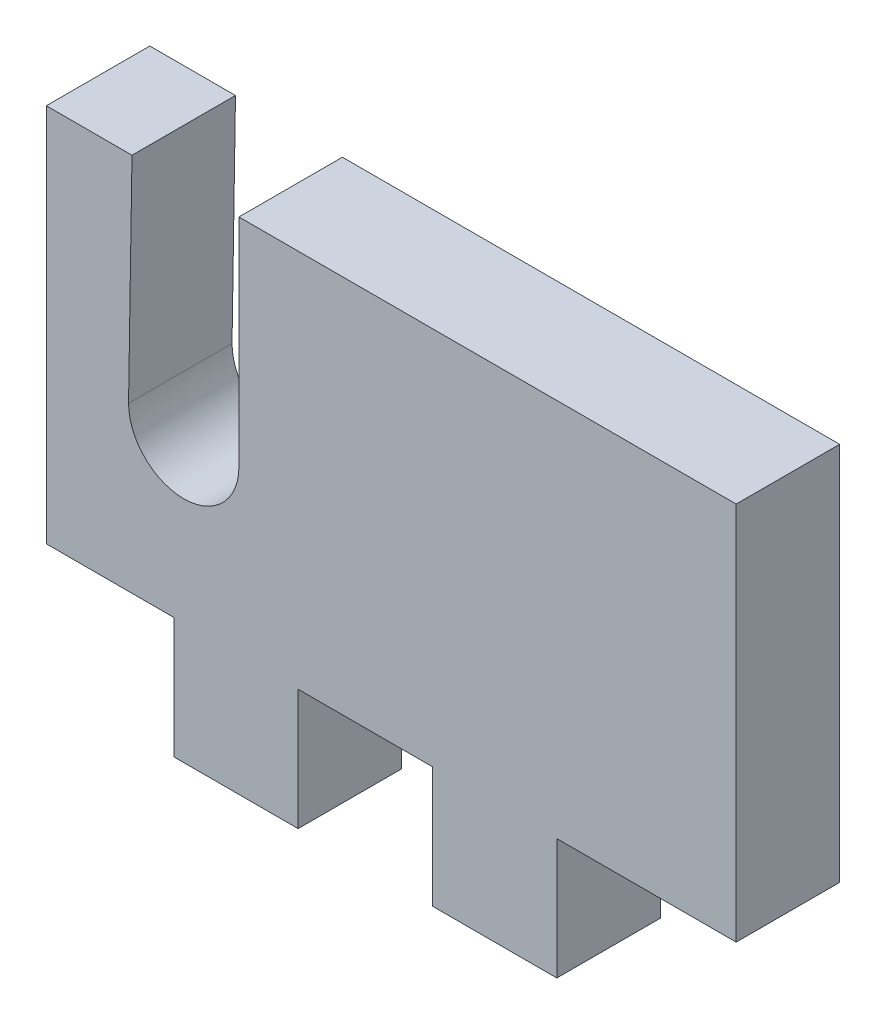
SolidWorks part; units mm, degrees
ref_plane "Front Plane" through (0, 0, 0) normal (0, 0, 1) x (1, 0, 0)
ref_plane "Top Plane" through (0, 0, 0) normal (0, 1, 0) x (1, 0, 0)
ref_plane "Right Plane" through (0, 0, 0) normal (1, 0, 0) x (0, 0, -1)
sketch "Sketch1" plane through (0, 0, 0) normal (0, 0, 1) x (1, 0, 0)
  line L1 (-7.8838, 4.334) -> (12.1162, 4.334)
  line L2 (-7.8838, 4.334) -> (-7.8838, -10.166)
  line L3 (-7.8838, -10.166) -> (12.1162, -10.166)
  line L4 (12.1162, 4.334) -> (12.1162, -10.166)
  dimension "D1" = 20
  dimension "D2" = 14.5
extrude "Boss-Extrude1" add sketch "Sketch1" along normal blind 3
sketch "Sketch2" plane through (0, 0, 3) normal (0, 0, 1) x (1, 0, 0)
  line L0 (-7.8838, -10.166) -> (12.1162, -10.166) construction
  line L1 (-7.8838, -10.166) -> (-4.1838, -10.166)
  line L2 (-7.8838, -10.166) -> (-7.8838, -6.666)
  line L3 (-7.8838, -6.666) -> (-4.1838, -6.666)
  line L4 (-4.1838, -10.166) -> (-4.1838, -6.666)
  line L5 (-0.5838, -10.166) -> (3.3162, -10.166)
  line L6 (-0.5838, -10.166) -> (-0.5838, -6.666)
  line L7 (-0.5838, -6.666) -> (3.3162, -6.666)
  line L8 (3.3162, -10.166) -> (3.3162, -6.666)
  line L9 (12.1162, -10.166) -> (12.1162, 4.334) construction
  line L10 (6.9162, -10.166) -> (12.1162, -10.166)
  line L11 (6.9162, -10.166) -> (6.9162, -6.666)
  line L12 (6.9162, -6.666) -> (12.1162, -6.666)
  line L13 (12.1162, -10.166) -> (12.1162, -6.666)
  dimension "D1" = 3.7
  dimension "D2" = 3.5
  dimension "D3" = 3.6
  dimension "D4" = 3.9
  dimension "D5" = 3.5
  dimension "D6" = 3.6
  dimension "D7" = 3.5
extrude "Cut-Extrude1" cut sketch "Sketch2" against normal blind 3
sketch "Sketch3" plane through (0, 0, 3) normal (0, 0, 1) x (1, 0, 0)
  line L0 (-3.8501, 4.334) -> (-3.8501, -1.9382) construction
  line L1 (12.1162, 4.334) -> (-7.8838, 4.334) construction
  line L2 (-2.3001, 4.334) -> (-2.3001, -1.9382)
  line L3 (-5.4001, 4.334) -> (-5.4001, -1.9382)
  arc A0 (-2.3001, 4.334) -> (-5.4001, 4.334) centre (-3.8501, 4.334) ccw
  arc A1 (-5.4001, -1.9382) -> (-2.3001, -1.9382) centre (-3.8501, -1.9382) ccw
  point P4 (-3.8501, 1.1979)
  point P9 (-4.8893, 4.334)
  dimension "D1" = 3.1
extrude "Cut-Extrude2" cut sketch "Sketch3" against normal blind 3
sketch "Sketch4" plane through (0, 0, 3) normal (0, 0, 1) x (1, 0, 0)
  line L0 (-5.4001, 4.334) -> (-5.5001, -1.9451)
  line L1 (-2.3001, -1.9382) -> (-5.4001, 4.334)
  arc A0 (-5.5001, -1.9451) -> (-2.3001, -1.9382) centre (-3.9001, -1.9417) ccw
  dimension "D1" = 0.1
extrude "Cut-Extrude3" cut sketch "Sketch4" against normal blind 3
